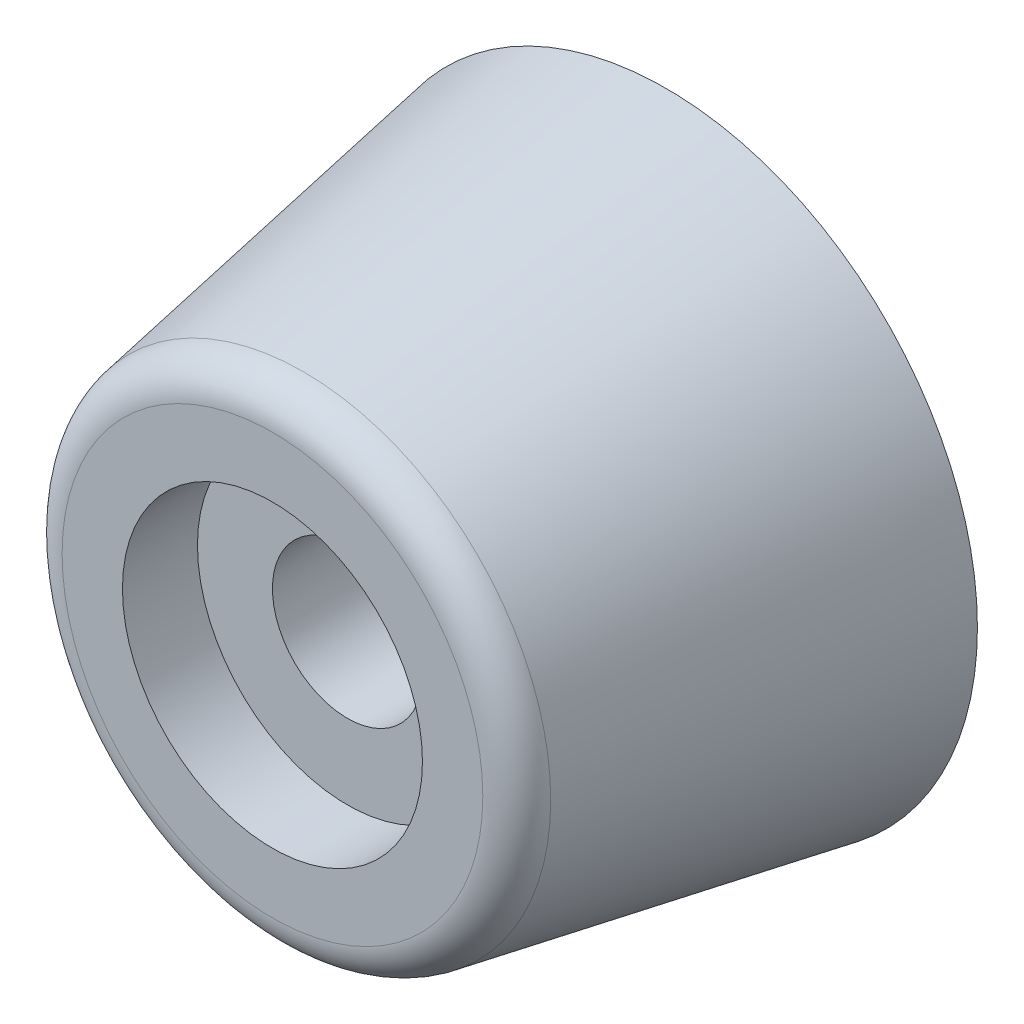
SolidWorks part; units mm, degrees
ref_plane "Plan de face" through (0, 0, 0) normal (0, 0, 1) x (1, 0, 0)
ref_plane "Plan de dessus" through (0, 0, 0) normal (0, 1, 0) x (1, 0, 0)
ref_plane "Plan de droite" through (0, 0, 0) normal (1, 0, 0) x (0, 0, -1)
sketch "Esquisse1" plane through (0, 0, 0) normal (0, 0, 1) x (1, 0, 0)
  circle A0 centre (0, 0) radius 8.3
  dimension "D1" = 16.6
extrude "Boss.-Extru.1" add sketch "Esquisse1" along normal blind 10.5 draft 10
sketch "Esquisse2" plane through (0, 0, 10.5) normal (0, 0, 1) x (1, 0, 0)
  circle A0 centre (0, 0) radius 4
  dimension "D1" = 8
extrude "Enlèv. mat.-Extru.1" cut sketch "Esquisse2" against normal blind 2
sketch "Esquisse3" plane through (0, 0, 8.5) normal (0, 0, 1) x (1, 0, 0)
  circle A0 centre (0, 0) radius 2
  dimension "D1" = 4
extrude "Enlèv. mat.-Extru.2" cut sketch "Esquisse3" against normal blind 14
fillet "Congé1" radius 1 1 edges at (6.4486, 0, 10.5)
